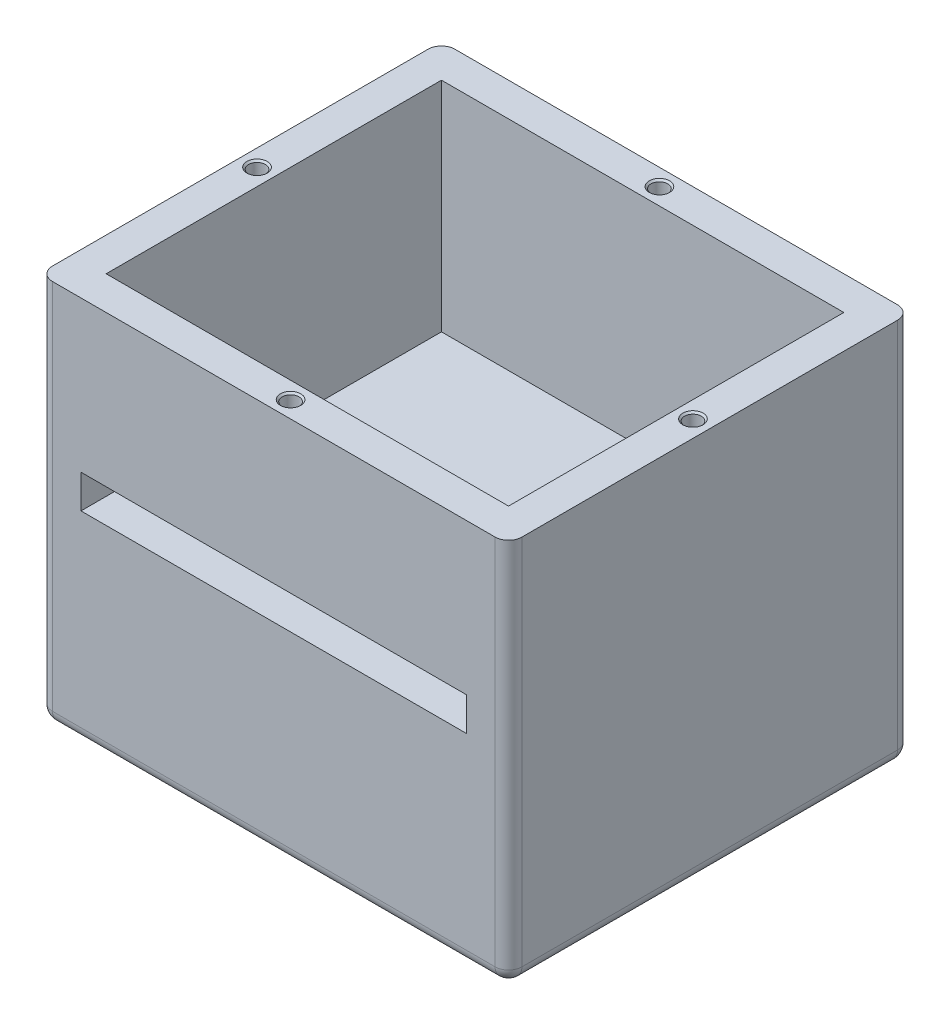
SolidWorks part; units mm, degrees
ref_plane "前视基准面" through (0, 0, 0) normal (0, 0, 1) x (1, 0, 0)
ref_plane "上视基准面" through (0, 0, 0) normal (0, 1, 0) x (1, 0, 0)
ref_plane "右视基准面" through (0, 0, 0) normal (1, 0, 0) x (0, 0, -1)
other "Configuration Table"
sketch "Box_top_view" plane through (0, 0, 0) normal (0, 1, 0) x (1, 0, 0)
  line L1 (-70, -60) -> (70, -60)
  line L2 (-70, -60) -> (-70, 60)
  line L3 (-70, 60) -> (70, 60)
  line L4 (70, -60) -> (70, 60)
  point P4 (-70, 0)
  point P6 (0, 60)
  dimension "D1" = 140
  dimension "D2" = 120
extrude "Box_extrude_part" add sketch "Box_top_view" along normal blind 110 and the other way blind 5
sketch "Scissor_crossSection" plane through (0, 0, 60) normal (0, 0, 1) x (1, 0, 0)
  line L0 (-70, -5) -> (70, -5) construction
  line L1 (-57.5, 65) -> (57.5, 65)
  line L2 (-57.5, 65) -> (-57.5, 55)
  line L3 (-57.5, 55) -> (57.5, 55)
  line L4 (57.5, 65) -> (57.5, 55)
  point P4 (0, 65)
  point P6 (57.5, 60)
  dimension "D1" = 10
  dimension "D2" = 115
  dimension "D3" = 65
sketch "Inner_box_cut" plane through (0, 110, 0) normal (0, 1, 0) x (1, 0, 0)
  line L1 (-60, 50) -> (60, 50)
  line L2 (-60, 50) -> (-60, -50)
  line L3 (-60, -50) -> (60, -50)
  line L4 (60, 50) -> (60, -50)
  point P5 (0, 50)
  point P7 (-60, 0)
  dimension "D1" = 120
  dimension "D2" = 100
extrude "Inner_box_cut_1" cut sketch "Inner_box_cut" against normal blind 65
extrude "Scissor_corssSection_cut" cut sketch "Scissor_crossSection" against normal blind 10
sketch "Shaft_location" plane through (0, 45, 0) normal (0, 1, 0) x (1, 0, 0)
  line L0 (0, 21.009) -> (0, -18.7201) construction
  circle A0 centre (15, 0) radius 7.5
  circle A1 centre (-15, 0) radius 7.5
  dimension "D1" = 15
  dimension "D2" = 15
extrude "Shaft_location_cut" cut sketch "Shaft_location" against normal blind 40 contours A0 | A1
sketch "Sketch2" plane through (0, 45, 0) normal (0, 1, 0) x (1, 0, 0)
  line L0 (0, 22.1535) -> (0, -20.3551) construction
  circle A1 centre (-15, 0) radius 14
  circle A2 centre (15, 0) radius 14
  dimension "D1" = 28
extrude "Bearing_location_cut1" cut sketch "Sketch2" against normal blind 10
sketch "Sketch8" plane through (0, 45, 0) normal (0, 1, 0) x (1, 0, 0)
  circle A0 centre (-15, 0) radius 9.5
  dimension "D1" = 19
extrude "Bearing_location_cut2" cut sketch "Sketch8" against normal blind 35
sketch "Hole_location" plane through (0, 110, 0) normal (0, 1, 0) x (1, 0, 0)
  line L0 (0, 30.1647) -> (0, -21.1725) construction
  line L1 (-34.0069, 0) -> (33.6799, 0) construction
  point P5 (-65, 0)
  point P6 (0, 55)
  dimension "D1" = 65
  dimension "D2" = 55
hole_wizard "M6 Tapped Hole3" positions "3DSketch3" profile "Sketch7" tap size "M6" standard "ISO"
sketch3d "3DSketch3"
  point P0 (0, 110, -55)
  point P3 (-65, 110, 0)
cosmetic thread "Hole Thread7" parameters "D1"=10, "D2"=6
cosmetic thread "Hole Thread8" parameters "D1"=10, "D2"=6
sketch "Sketch7" plane through (0, 110, -55) normal (1, 0, 0) x (0, 0, 1)
  line L0 (0, 0) -> (0, 14.5022)
  line L1 (0, 14.5022) -> (2.5, 13)
  line L2 (2.5, 13) -> (2.5, 0.525)
  line L3 (2.5, 0.525) -> (3.025, 0)
  line L5 (3.025, 0) -> (0, 0)
  line L6 (-2.5, 0.525) -> (-3.025, 0) construction
  line L10 (0, 14.5022) -> (-2.5, 13) construction
  line L11 (0, -6.35) -> (0, 107.95) construction
  dimension "Tap Drill Dia." = 5
  dimension "Tap Drill Depth" = 13
  dimension "Near C'Sink Dia." = 6.05
  dimension "Near C'Sink Angle" = 90
  dimension "Drill Angle" = 118
mirror "M6_hole_mirror" about plane through (0, 0, 0) normal (1, 0, 0) of "M6 Tapped Hole3" second plane through (0, 0, 0) second plane normal (0, 0, 1)
fillet "Edges_fillet" radius 4 8 edges at (-70, -5, 0) (0, -5, -60) (0, -5, 60) (70, -5, 0) (-70, 52.5, -60) (70, 52.5, -60) (70, 52.5, 60) (-70, 52.5, 60)
